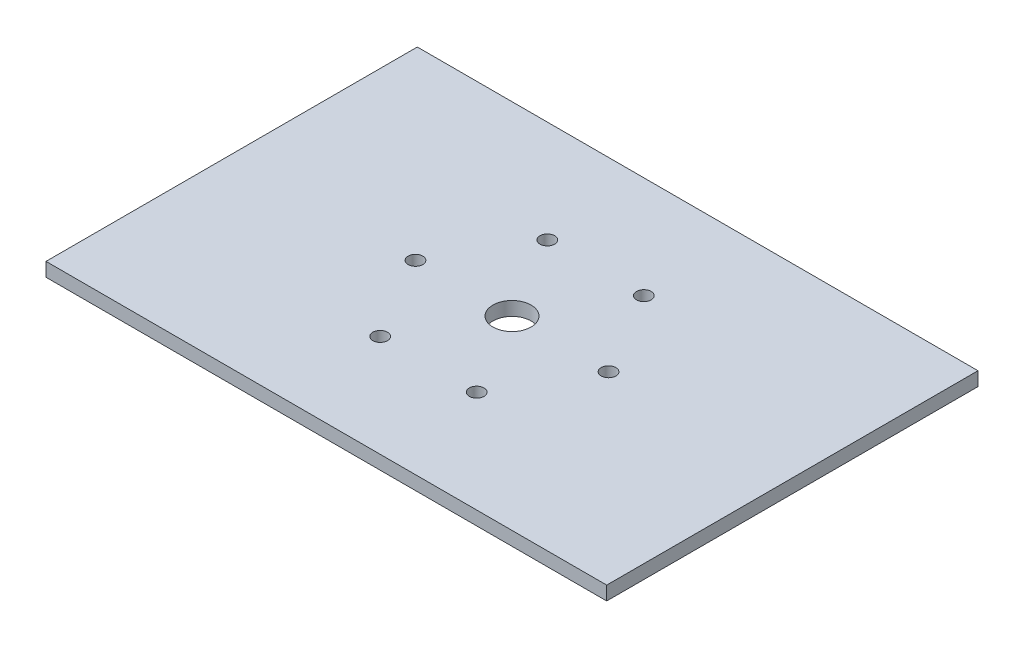
SolidWorks part; units mm, degrees
material "Carbon Fiber"
ref_plane "Front Plane" through (0, 0, 0) normal (0, 0, 1) x (1, 0, 0)
ref_plane "Top Plane" through (0, 0, 0) normal (0, 1, 0) x (1, 0, 0)
ref_plane "Right Plane" through (0, 0, 0) normal (1, 0, 0) x (0, 0, -1)
sketch "Sketch1" plane through (0, 0, 0) normal (0, 1, 0) x (1, 0, 0)
  line L0 (61, 80.79) -> (61, 0) construction
  line L1 (0, 0) -> (122, 0)
  line L2 (0, 0) -> (0, 80.79)
  line L3 (0, 80.79) -> (122, 80.79)
  line L4 (122, 0) -> (122, 80.79)
  line L5 (0, 40.395) -> (122, 40.395) construction
  circle A0 centre (40, 40.395) radius 1.6
  circle A1 centre (50.5, 58.5815) radius 1.6
  circle A2 centre (71.5, 58.5815) radius 1.6
  circle A3 centre (82, 40.395) radius 1.6
  circle A4 centre (61, 40.395) radius 4.15
  circle A5 centre (71.5, 22.2085) radius 1.6
  circle A6 centre (50.5, 22.2085) radius 1.6
  point P11 (61, 40.395)
  dimension "D3" = 3.2
  dimension "D4" = 21
  dimension "D6" = 8.3
  dimension "D1" = 122
  dimension "D2" = 80.79
  dimension "D5" = 6
extrude "Boss-Extrude1" add sketch "Sketch1" along normal blind 3
